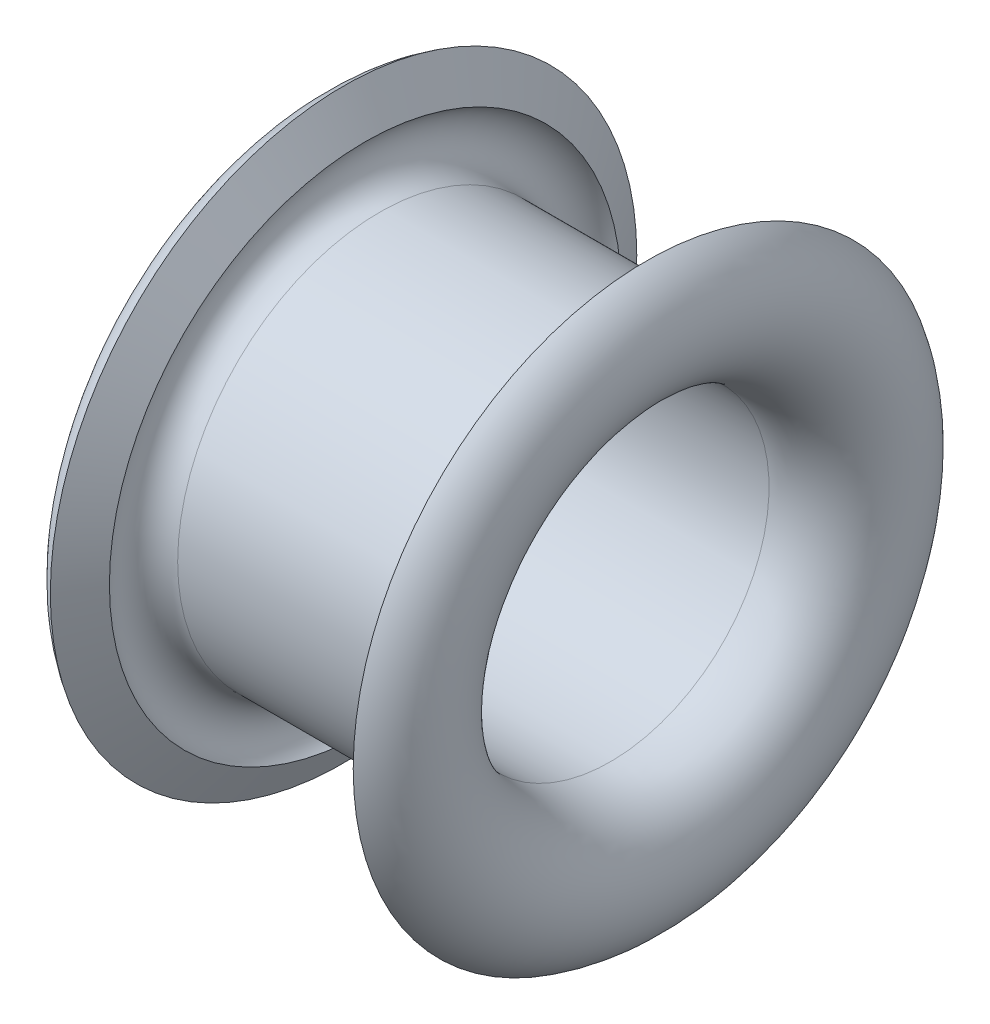
SolidWorks part; units mm, degrees
material "Латунь"
ref_plane "Спереди" through (0, 0, 0) normal (0, 0, 1) x (1, 0, 0)
ref_plane "Сверху" through (0, 0, 0) normal (0, 1, 0) x (1, 0, 0)
ref_plane "Справа" through (0, 0, 0) normal (1, 0, 0) x (0, 0, -1)
sketch "Эскиз1" plane through (0, 0, 0) normal (0, 0, 1) x (1, 0, 0)
  line L0 (0, 1.1) -> (0.8, 1.1)
  line L1 (0, 1.4) -> (0.8, 1.4)
  line L2 (0, 1.1) -> (0, 1.4)
  line L3 (0.9, 1.7732) -> (1.05, 2.033)
  line L4 (0, 0) -> (0.8, 0) construction
  arc A0 (0.8, 1.1) -> (1.05, 2.033) centre (0.8, 1.6) ccw
  arc A1 (0.8, 1.4) -> (0.9, 1.7732) centre (0.8, 1.6) ccw
  dimension "D3" = 0.5
  dimension "D1" = 1.1
  dimension "D2" = 0.9
  dimension "D4" = 0.1
  dimension "D5" = 0.3
revolve "Повернуть1" add sketch "Эскиз1" angle 360 about L4
mirror "Зеркальное отражение1" about plane through (0, 1.1, 0) normal (1, 0, 0) of "Повернуть1"
